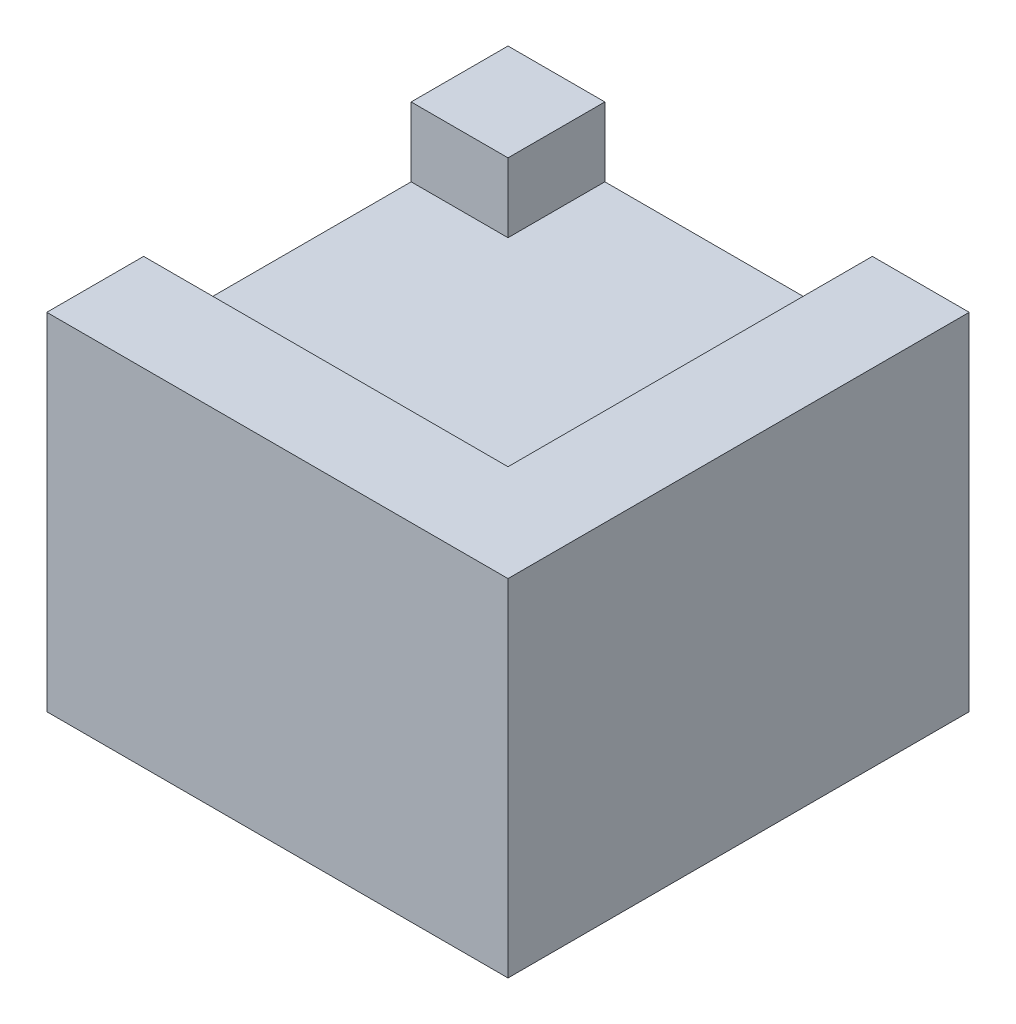
SolidWorks part; units mm, degrees
ref_plane "Front Plane" through (0, 0, 0) normal (0, 0, 1) x (1, 0, 0)
ref_plane "Top Plane" through (0, 0, 0) normal (0, 1, 0) x (1, 0, 0)
ref_plane "Right Plane" through (0, 0, 0) normal (1, 0, 0) x (0, 0, -1)
sketch "Sketch1" plane through (0, 0, 0) normal (0, 1, 0) x (1, 0, 0)
  line L1 (-15.875, 15.875) -> (15.875, 15.875)
  line L2 (-15.875, 15.875) -> (-15.875, -15.875)
  line L3 (-15.875, -15.875) -> (15.875, -15.875)
  line L4 (15.875, 15.875) -> (15.875, -15.875)
  line L5 (-15.875, 15.875) -> (15.875, -15.875) construction
  line L6 (-15.875, -15.875) -> (15.875, 15.875) construction
  point P0 (0, 0)
  dimension "D1" = 31.75
  dimension "D2" = 31.75
extrude "Boss-Extrude1" add sketch "Sketch1" along normal blind 19.05
sketch "Sketch2" plane through (0, 19.05, 0) normal (0, 1, 0) x (1, 0, 0)
  line L0 (-9.2075, 15.875) -> (-9.2075, 9.2075)
  line L1 (15.875, 15.875) -> (-15.875, 15.875) construction
  line L2 (-9.2075, 9.2075) -> (-15.875, 9.2075)
  line L3 (-15.875, 15.875) -> (-15.875, -15.875) construction
  line L4 (-15.875, 9.2075) -> (-15.875, 15.875)
  line L5 (-15.875, 15.875) -> (-9.2075, 15.875)
  line L6 (-15.875, -9.2075) -> (9.2075, -9.2075)
  line L7 (9.2075, -9.2075) -> (9.2075, 15.875)
  line L8 (9.2075, 15.875) -> (15.875, 15.875)
  line L9 (15.875, 15.875) -> (15.875, -15.875)
  line L10 (15.875, -15.875) -> (-15.875, -15.875)
  line L11 (-15.875, -15.875) -> (-15.875, -9.2075)
  line L12 (-15.875, 9.2075) -> (0, 0) construction
  line L13 (0, 0) -> (-15.875, -9.2075) construction
  line L14 (-14.8163, 0.3554) -> (-14.8163, 0.3963) construction
  line L15 (-9.2075, 15.875) -> (0, 0) construction
  line L16 (0, 0) -> (9.2075, 15.875) construction
  dimension "D1" = 18.415
  dimension "D2" = 18.415
extrude "Boss-Extrude2" add sketch "Sketch2" along normal blind 4.7625
